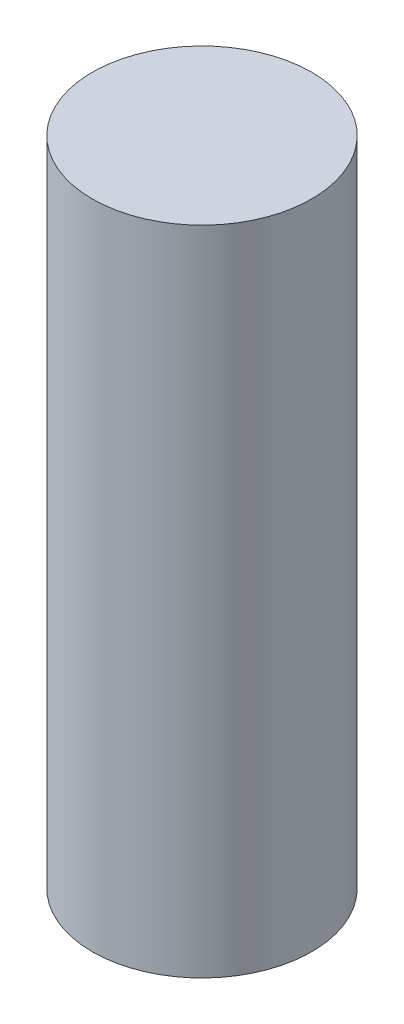
SolidWorks part; units mm, degrees
ref_plane "Alzado" through (0, 0, 0) normal (0, 0, 1) x (1, 0, 0)
ref_plane "Planta" through (0, 0, 0) normal (0, 1, 0) x (1, 0, 0)
ref_plane "Vista lateral" through (0, 0, 0) normal (1, 0, 0) x (0, 0, -1)
sketch "Croquis1" plane through (0, 0, 0) normal (0, 1, 0) x (1, 0, 0)
  circle A0 centre (0, 0) radius 2.525
  dimension "D1" = 5.05
extrude "Saliente-Extruir1" add sketch "Croquis1" along normal mid plane 15
